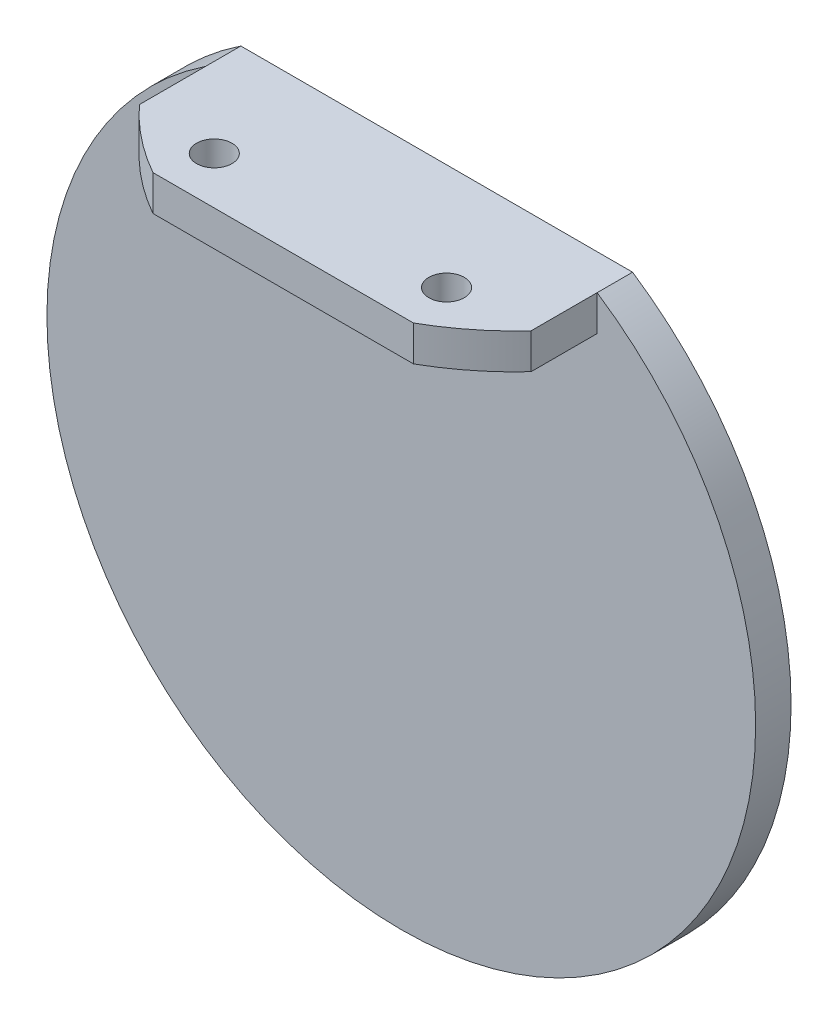
SolidWorks part; units mm, degrees
ref_plane "Plan de face" through (0, 0, 0) normal (0, 0, 1) x (1, 0, 0)
ref_plane "Plan de dessus" through (0, 0, 0) normal (0, 1, 0) x (1, 0, 0)
ref_plane "Plan de droite" through (0, 0, 0) normal (1, 0, 0) x (0, 0, -1)
sketch "Esquisse1" plane through (0, 0, 0) normal (0, 0, 1) x (1, 0, 0)
  line L0 (-16.5831, 25) -> (16.5831, 25)
  circle A0 centre (0, 0) radius 30
  dimension "D1" = 60
  dimension "D2" = 25
extrude "Boss.-Extru.1" add sketch "Esquisse1" along normal blind 3 contours L0 A0
sketch "Esquisse2" plane through (0, 0, 0) normal (0, 0, -1) x (-1, 0, 0)
  line L0 (-16.5831, 22) -> (16.5831, 22)
  line L1 (16.5831, 25) -> (-16.5831, 25)
  line L2 (16.5831, 25) -> (-16.5831, 25)
  line L3 (-16.5831, 25) -> (-16.5831, 22)
  line L4 (16.5831, 25) -> (16.5831, 22)
  arc A1 (-16.5831, 25) -> (16.5831, 25) centre (0, 0) ccw
  arc A2 (-16.5831, 25) -> (16.5831, 25) centre (0, 0) ccw
  line M3 (16.5831, 25) -> (-16.5831, 25)
  arc M4 (-16.5831, 25) -> (16.5831, 25) centre (0, 0) ccw
  dimension "D2" = 3
  dimension "D1" = 0
extrude "Boss.-Extru.2" add sketch "Esquisse2" against normal blind 10 from offset 3 contours L0 M4 M3 offset against normal yes
sketch "Esquisse3" plane through (0, 25, 0) normal (0, 1, 0) x (1, 0, 0)
  line L0 (11.0247, -13) -> (16.5831, -13)
  line L6 (16.5831, 0) -> (-16.5831, 0)
  line L7 (-16.5831, 0) -> (-16.5831, -3)
  line L8 (-16.5831, -3) -> (-16.5831, -13)
  line L9 (-16.5831, -13) -> (16.5831, -13)
  line L10 (16.5831, -13) -> (16.5831, -3)
  line L11 (16.5831, -3) -> (16.5831, 0)
  line L14 (-16.5831, -8.5899) -> (-16.5831, -13)
  line L15 (-16.5831, -13) -> (-11.0209, -13)
  line L16 (16.5831, -13) -> (16.5831, -8.594)
  arc A0 (-16.5831, -8.5899) -> (-11.0209, -13) centre (0.0019, 6.615) ccw
  arc A1 (11.0247, -13) -> (16.5831, -8.594) centre (0.0019, 6.615) ccw
  dimension "D1" = 0
extrude "Enlèv. mat.-Extru.1" cut sketch "Esquisse3" against normal through all
sketch "Esquisse4" plane through (0, 22, 0) normal (0, -1, 0) x (1, 0, 0)
  line L0 (-16.5831, 8.5899) -> (-16.5831, 3) construction
  line L1 (16.5831, 3) -> (-16.5831, 3) construction
  line L2 (0, 18.468) -> (0, -0.5057) construction
  circle A0 centre (-9.8331, 9) radius 1.5
  circle A1 centre (9.8331, 9) radius 1.5
  dimension "D1" = 6.75
  dimension "D2" = 6
extrude "Enlèv. mat.-Extru.2" cut sketch "Esquisse4" against normal through all
